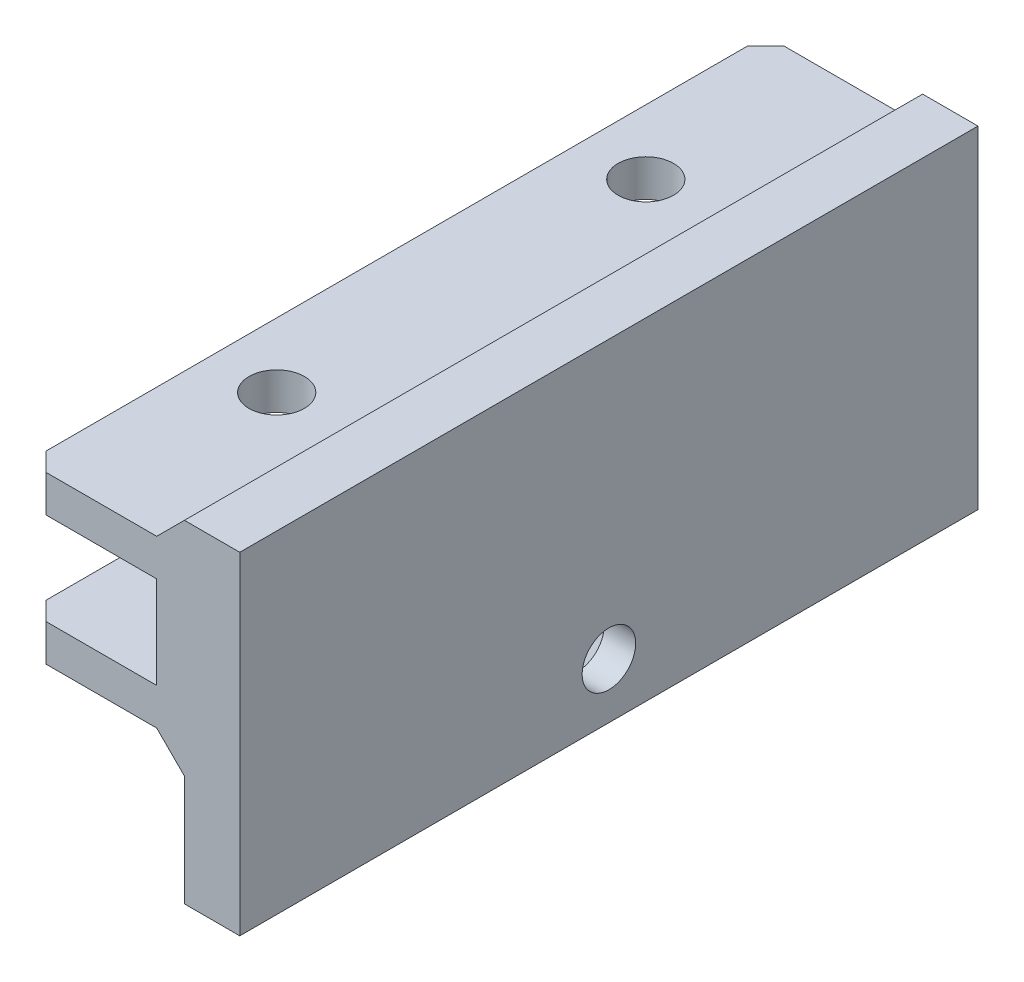
SolidWorks part; units mm, degrees
material "ABS"
ref_plane "Alzado" through (0, 0, 0) normal (1, 0, 0) x (0, 1, 0)
ref_plane "Planta" through (0, 0, 0) normal (0, 0, 1) x (0, 1, 0)
ref_plane "Vista lateral" through (0, 0, 0) normal (0, 1, 0) x (-1, 0, 0)
sketch "Croquis1" plane through (0, 0, 0) normal (0, 0, 1) x (0, 1, 0)
  line L0 (0, 0) -> (0, 11.5) construction
  line L1 (-6, 0) -> (6, 0)
  line L2 (6, 0) -> (6, 3)
  line L3 (6, 3) -> (4.5, 4.5)
  line L4 (4.5, 4.5) -> (4.5, 11.5)
  line L5 (4.5, 11.5) -> (2.5, 11.5)
  line L6 (-2.5, 4.5) -> (2.5, 4.5)
  line L7 (2.5, 4.5) -> (2.5, 11.5)
  line L8 (-6, 0) -> (-6, 3)
  line L9 (-6, 3) -> (-4.5, 4.5)
  line L10 (-4.5, 4.5) -> (-4.5, 11.5)
  line L11 (-4.5, 11.5) -> (-2.5, 11.5)
  line L12 (-2.5, 4.5) -> (-2.5, 11.5)
  point P16 (0, 4.5)
  dimension "D1" = 4.5
  dimension "D2" = 11.5
  dimension "D3" = 2.5
  dimension "D4" = 6
  dimension "D5" = 2
  dimension "D6" = 45
extrude "Saliente-Extruir1" add sketch "Croquis1" along normal mid plane 40
sketch "Croquis2" plane through (0, 4.5, 0) normal (0, 1, 0) x (-1, 0, 0)
  line L0 (8, 20) -> (8, -20) construction
  line L1 (4.5, 20) -> (11.5, 20) construction
  line L2 (4.5, -20) -> (11.5, -20) construction
  point P6 (8, 10)
  point P7 (8, -10)
  point P8 (8, 0)
  dimension "D1" = 10
  dimension "D2" = 20
hole_wizard "Taladro de margen para M31" positions "Croquis2" profile "Croquis3" hole size "M3" standard "Ansi Metric" end condition through all
sketch "Croquis3" plane through (-8, 4.5, -10) normal (1, 0, 0) x (0, 0, 1)
  line L0 (0, 0) -> (0, 10.5)
  line L1 (0, 10.5) -> (1.5, 10.5)
  line L2 (1.5, 10.5) -> (1.5, 0)
  line L5 (1.5, 0) -> (0, 0)
  line L11 (0, -6.35) -> (0, 107.95) construction
  dimension "Diámetro de taladro hasta el siguiente" = 3
  dimension "Profundidad de taladro hasta el siguiente" = 10.5
chamfer "Chaflán2" distance 1 angle 45 4 edges at (-11.5, -3.5, -20) (-11.5, 3.5, -20) (-11.5, 3.5, 20) (-11.5, -3.5, 20)
sketch "Croquis4" plane through (0, -6, 0) normal (0, -1, 0) x (1, 0, 0)
  line L4 (-3, -20) -> (0, -20)
  line L5 (0, -20) -> (0, 20)
  line L6 (0, 20) -> (-3, 20)
  line L7 (-3, 20) -> (-3, -20)
  line L8 (-3, -20) -> (0, -20)
  line L9 (0, -20) -> (0, 20)
  line L10 (0, 20) -> (-3, 20)
  line L11 (-3, 20) -> (-3, -20)
  dimension "D1" = 0
extrude "Saliente-Extruir2" add sketch "Croquis4" along normal blind 6
sketch "Croquis5" plane through (-3, 0, 0) normal (-1, 0, 0) x (0, -1, 0)
  line L0 (12, 20) -> (12, -20) construction
  point P0 (9, 0)
  point P3 (0, 0)
  dimension "D1" = 3
hole_wizard "Avellanado para tornillo con cabeza ovalada de M2.51" positions "Croquis5" profile "Croquis6" countersink size "M2.5" standard "Ansi Metric" end condition through all
sketch "Croquis6" plane through (-3, -9, 0) normal (0, 1, 0) x (0, 0, 1)
  line L0 (0, 0) -> (0, 3)
  line L1 (0, 3) -> (1.45, 3)
  line L2 (1.45, 3) -> (1.45, 1.3)
  line L3 (1.45, 1.3) -> (2.75, 0)
  line L5 (2.75, 0) -> (0, 0)
  line L6 (-1.45, 1.3) -> (-2.75, 0) construction
  line L11 (0, -6.35) -> (0, 107.95) construction
  dimension "Diámetro de taladro hasta el siguiente" = 2.9
  dimension "Profundidad de taladro hasta el siguiente" = 3
  dimension "Diámetro de avellanado cercano" = 5.5
  dimension "Ángulo de avellanado cercano" = 90
